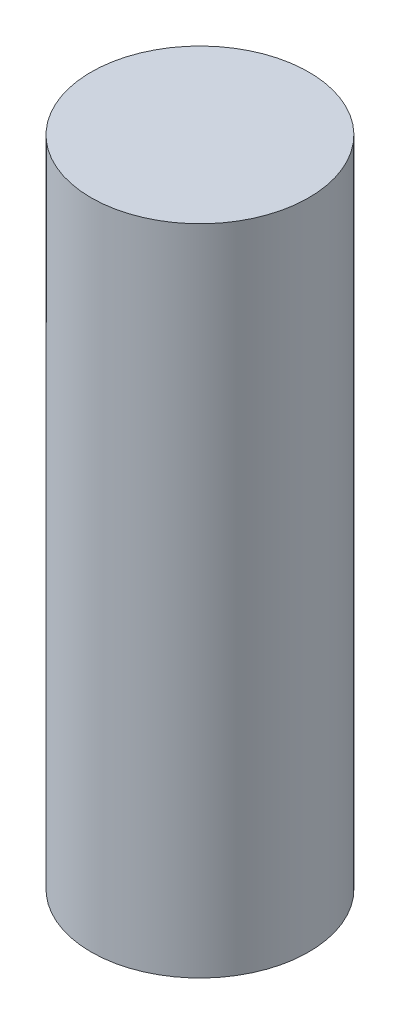
SolidWorks part; units mm, degrees
ref_plane "정면" through (0, 0, 0) normal (0, 0, 1) x (1, 0, 0)
ref_plane "윗면" through (0, 0, 0) normal (0, 1, 0) x (1, 0, 0)
ref_plane "우측면" through (0, 0, 0) normal (1, 0, 0) x (0, 0, -1)
sketch "스케치1" plane through (0, 0, 0) normal (0, 1, 0) x (1, 0, 0)
  circle A0 centre (0, 0) radius 5
  dimension "D1" = 10
extrude "보스-돌출1" add sketch "스케치1" along normal blind 30
